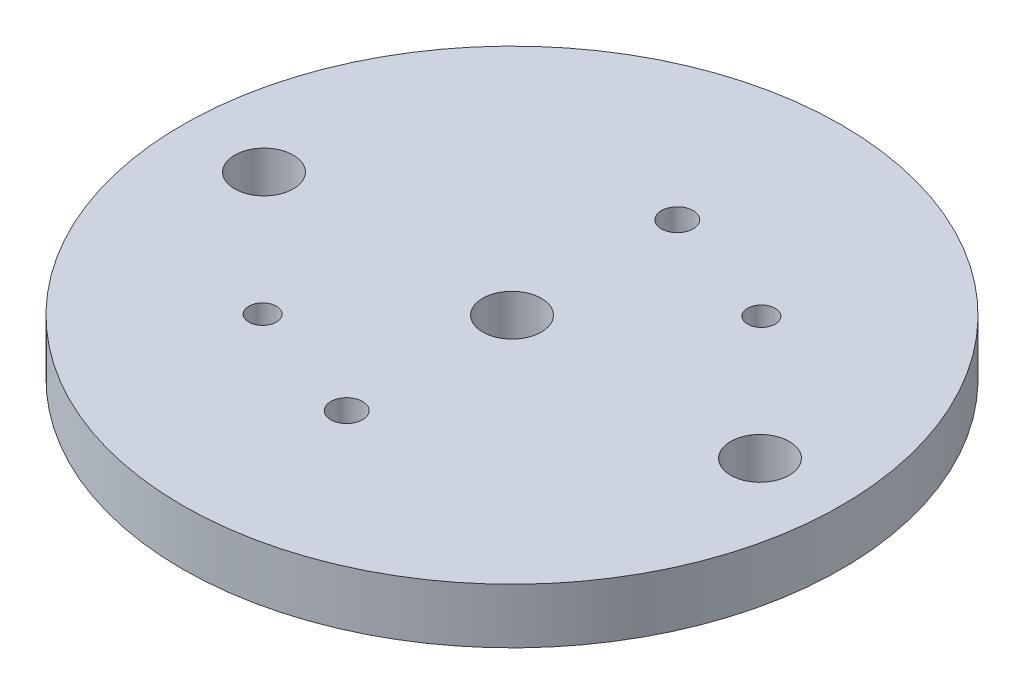
SolidWorks part; units mm, degrees
ref_plane "Front Plane" through (0, 0, 0) normal (0, 0, 1) x (1, 0, 0)
ref_plane "Top Plane" through (0, 0, 0) normal (0, 1, 0) x (1, 0, 0)
ref_plane "Right Plane" through (0, 0, 0) normal (1, 0, 0) x (0, 0, -1)
sketch "Sketch1" plane through (0, 0, 0) normal (0, 1, 0) x (1, 0, 0)
  circle A0 centre (0, 0) radius 37.973
  dimension "D1" = 75.946
extrude "Boss-Extrude1" add sketch "Sketch1" along normal mid plane 6.35
hole_wizard "H (0.266) Diameter Hole1" positions "Sketch2" profile "Sketch3" hole size "H" standard "ANSI Inch" end condition through all
sketch "Sketch2" plane through (0, 3.175, 0) normal (0, 1, 0) x (1, 0, 0)
  line L0 (-28.575, 0) -> (28.575, 0) construction
  point P0 (-28.575, 0)
  point P2 (28.575, 0)
  dimension "D1" = 57.15
sketch "Sketch3" plane through (-28.575, 3.175, 0) normal (1, 0, 0) x (0, 0, 1)
  line L0 (0, 0) -> (0, 6.35)
  line L1 (0, 6.35) -> (3.3782, 6.35)
  line L2 (3.3782, 6.35) -> (3.3782, 0)
  line L5 (3.3782, 0) -> (0, 0)
  line L11 (0, -6.35) -> (0, 107.95) construction
  dimension "Thru Hole Dia." = 6.7564
  dimension "Thru Hole Depth" = 6.35
hole_wizard "#27 (0.144) Diameter Hole1" positions "Sketch7" profile "Sketch8" hole size "#27" standard "ANSI Inch" end condition through all
sketch "Sketch7" plane through (0, 3.175, 0) normal (0, 1, 0) x (1, 0, 0)
  line L0 (0, -19.05) -> (0, 19.05) construction
  point P0 (0, 19.05)
  point P2 (0, -19.05)
  dimension "D1" = 38.1
sketch "Sketch8" plane through (0, 3.175, -19.05) normal (1, 0, 0) x (0, 0, 1)
  line L0 (0, 0) -> (0, 6.35)
  line L1 (0, 6.35) -> (1.8288, 6.35)
  line L2 (1.8288, 6.35) -> (1.8288, 0)
  line L5 (1.8288, 0) -> (0, 0)
  line L11 (0, -6.35) -> (0, 107.95) construction
  dimension "Thru Hole Dia." = 3.6576
  dimension "Thru Hole Depth" = 6.35
hole_wizard "1/8 (0.125) Diameter Hole1" positions "Sketch9" profile "Sketch10" hole size "1/8" standard "ANSI Inch" end condition through all
sketch "Sketch9" plane through (0, 3.175, 0) normal (0, 1, 0) x (1, 0, 0)
  line L0 (-14.4698, -14.2663) -> (14.4698, 14.2663) construction
  circle A0 centre (0, 19.05) radius 1.8288 construction
  point P0 (14.4698, 14.2663)
  point P2 (-14.4698, -14.2663)
  dimension "D2" = 15.24
  dimension "D1" = 40.64
sketch "Sketch10" plane through (14.4698, 3.175, -14.2663) normal (1, 0, 0) x (0, 0, 1)
  line L0 (0, 0) -> (0, 6.35)
  line L1 (0, 6.35) -> (1.5875, 6.35)
  line L2 (1.5875, 6.35) -> (1.5875, 0)
  line L5 (1.5875, 0) -> (0, 0)
  line L11 (0, -6.35) -> (0, 107.95) construction
  dimension "Thru Hole Dia." = 3.175
  dimension "Thru Hole Depth" = 6.35
hole_wizard "H (0.266) Diameter Hole2" positions "Sketch11" profile "Sketch12" hole size "H" standard "ANSI Inch" end condition through all
sketch "Sketch11" plane through (0, 3.175, 0) normal (0, 1, 0) x (1, 0, 0)
  point P0 (0, 0)
sketch "Sketch12" plane through (0, 3.175, 0) normal (1, 0, 0) x (0, 0, 1)
  line L0 (0, 0) -> (0, 6.35)
  line L1 (0, 6.35) -> (3.3782, 6.35)
  line L2 (3.3782, 6.35) -> (3.3782, 0)
  line L5 (3.3782, 0) -> (0, 0)
  line L11 (0, -6.35) -> (0, 107.95) construction
  dimension "Thru Hole Dia." = 6.7564
  dimension "Thru Hole Depth" = 6.35
equation "\"airframeInnerDiameter\"=3"
equation "\"airframeBulkheadThickness\"=0.25"
equation "\"D1@Boss-Extrude1\"=\"airframeBulkheadThickness\""
equation "\"recoveryBayInnerDiameter\"=2.88"
equation "\"D1@Sketch1\"    = \"airframeInnerDiameter\"-0.01"
equation "\"threaded rod distance\"= 2.25"
equation "\"D1@Sketch2\"=\"threaded rod distance\""
